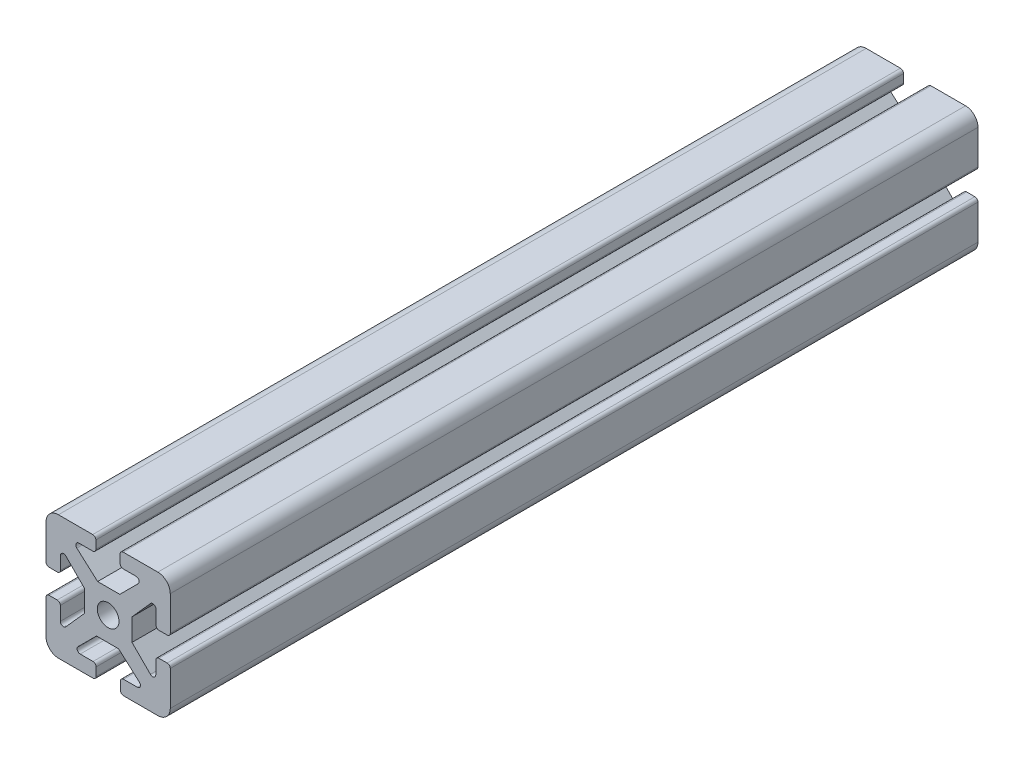
SolidWorks part; units mm, degrees
ref_plane "Front Plane" through (0, 0, 0) normal (0, 0, 1) x (1, 0, 0)
ref_plane "Top Plane" through (0, 0, 0) normal (0, 1, 0) x (1, 0, 0)
ref_plane "Right Plane" through (0, 0, 0) normal (1, 0, 0) x (0, 0, -1)
sketch "Sketch2" plane through (0, 0, 0) normal (0, 0, 1) x (1, 0, 0)
  line L0 (46.607, 139.3199) -> (233.0351, 139.3199) construction
  line L1 (0, 40) -> (40, 0) construction
  line L2 (0, 0) -> (40, 0) construction
  line L3 (0, 0) -> (0, 40) construction
  line L4 (0, 40) -> (40, 40) construction
  line L5 (40, 0) -> (40, 40) construction
  line L6 (0, 0) -> (40, 40) construction
  line L7 (19.4883, 27.6847) -> (23.7499, 27.6847)
  line L8 (23.7499, 27.6847) -> (29.6997, 33.625)
  line L9 (28.9931, 35.3327) -> (24.8456, 35.3327)
  line L10 (23.8456, 36.3327) -> (23.8456, 39)
  line L11 (24.8456, 40) -> (36, 40)
  line L12 (40, 36) -> (40, 24.9611)
  line L13 (39, 23.9611) -> (36.3883, 23.9611)
  line L14 (35.3883, 24.9611) -> (35.3883, 29.4086)
  line L15 (33.6417, 30.0739) -> (27.6847, 23.3888)
  line L16 (27.6847, 23.3888) -> (27.6847, 20.5117)
  line L17 (27.6847, 16.2501) -> (33.625, 10.3003)
  line L18 (30.0739, 6.3583) -> (23.3888, 12.3153)
  line L19 (27.6847, 20.5117) -> (27.6847, 16.2501)
  line L20 (35.3327, 11.0069) -> (35.3327, 15.1544)
  line L21 (36.3327, 16.1544) -> (39, 16.1544)
  line L22 (40, 15.1544) -> (40, 4)
  line L23 (36, 0) -> (24.9611, 0)
  line L24 (23.9611, 1) -> (23.9611, 3.6117)
  line L25 (24.9611, 4.6117) -> (29.4086, 4.6117)
  line L26 (23.3888, 12.3153) -> (20.5117, 12.3153)
  line L27 (16.2501, 12.3153) -> (10.3003, 6.375)
  line L28 (6.3583, 9.9261) -> (12.3153, 16.6112)
  line L29 (20.5117, 12.3153) -> (16.2501, 12.3153)
  line L30 (11.0069, 4.6673) -> (15.1544, 4.6673)
  line L31 (16.1544, 3.6673) -> (16.1544, 1)
  line L32 (15.1544, 0) -> (4, 0)
  line L33 (0, 4) -> (0, 15.0389)
  line L34 (1, 16.0389) -> (3.6117, 16.0389)
  line L35 (4.6117, 15.0389) -> (4.6117, 10.5914)
  line L36 (12.3153, 16.6112) -> (12.3153, 19.4883)
  line L37 (12.3153, 23.7499) -> (6.375, 29.6997)
  line L38 (9.9261, 33.6417) -> (16.6112, 27.6847)
  line L39 (12.3153, 19.4883) -> (12.3153, 23.7499)
  line L40 (4.6673, 28.9931) -> (4.6673, 24.8456)
  line L41 (3.6673, 23.8456) -> (1, 23.8456)
  line L42 (0, 24.8456) -> (0, 36)
  line L43 (4, 40) -> (15.0389, 40)
  line L44 (16.0389, 39) -> (16.0389, 36.3883)
  line L45 (15.0389, 35.3883) -> (10.5914, 35.3883)
  line L46 (16.6112, 27.6847) -> (19.4883, 27.6847)
  circle A1 centre (20, 20) radius 3.4925
  arc A2 (40, 24.9611) -> (39, 23.9611) centre (39, 24.9611) cw
  arc A3 (36.3883, 23.9611) -> (35.3883, 24.9611) centre (36.3883, 24.9611) cw
  arc A4 (24.8456, 35.3327) -> (23.8456, 36.3327) centre (24.8456, 36.3327) cw
  arc A5 (23.8456, 39) -> (24.8456, 40) centre (24.8456, 39) cw
  arc A6 (29.6997, 33.625) -> (28.9931, 35.3327) centre (28.9931, 34.3327) ccw
  arc A7 (35.3883, 29.4086) -> (33.6417, 30.0739) centre (34.3883, 29.4086) ccw
  arc A8 (40, 36) -> (36, 40) centre (36, 36) ccw
  arc A9 (35.3327, 15.1544) -> (36.3327, 16.1544) centre (36.3327, 15.1544) cw
  arc A10 (39, 16.1544) -> (40, 15.1544) centre (39, 15.1544) cw
  arc A11 (36, 0) -> (40, 4) centre (36, 4) ccw
  arc A12 (24.9611, 0) -> (23.9611, 1) centre (24.9611, 1) cw
  arc A13 (23.9611, 3.6117) -> (24.9611, 4.6117) centre (24.9611, 3.6117) cw
  arc A14 (29.4086, 4.6117) -> (30.0739, 6.3583) centre (29.4086, 5.6117) ccw
  arc A15 (33.625, 10.3003) -> (35.3327, 11.0069) centre (34.3327, 11.0069) ccw
  arc A16 (15.1544, 4.6673) -> (16.1544, 3.6673) centre (15.1544, 3.6673) cw
  arc A17 (16.1544, 1) -> (15.1544, 0) centre (15.1544, 1) cw
  arc A18 (0, 4) -> (4, 0) centre (4, 4) ccw
  arc A19 (0, 15.0389) -> (1, 16.0389) centre (1, 15.0389) cw
  arc A20 (3.6117, 16.0389) -> (4.6117, 15.0389) centre (3.6117, 15.0389) cw
  arc A21 (4.6117, 10.5914) -> (6.3583, 9.9261) centre (5.6117, 10.5914) ccw
  arc A22 (10.3003, 6.375) -> (11.0069, 4.6673) centre (11.0069, 5.6673) ccw
  arc A23 (4.6673, 24.8456) -> (3.6673, 23.8456) centre (3.6673, 24.8456) cw
  arc A24 (1, 23.8456) -> (0, 24.8456) centre (1, 24.8456) cw
  arc A25 (4, 40) -> (0, 36) centre (4, 36) ccw
  arc A26 (15.0389, 40) -> (16.0389, 39) centre (15.0389, 39) cw
  arc A27 (16.0389, 36.3883) -> (15.0389, 35.3883) centre (15.0389, 36.3883) cw
  arc A28 (10.5914, 35.3883) -> (9.9261, 33.6417) centre (10.5914, 34.3883) ccw
  arc A29 (6.375, 29.6997) -> (4.6673, 28.9931) centre (5.6673, 28.9931) ccw
  point P24 (40, 23.9611)
  point P31 (23.8456, 40)
  dimension "D1" = 40
  dimension "D3" = 1
  dimension "D4" = 4
  dimension "D2" = 40
  dimension "D5" = 4
extrude "Boss-Extrude1" add sketch "Sketch2" along normal blind 260
